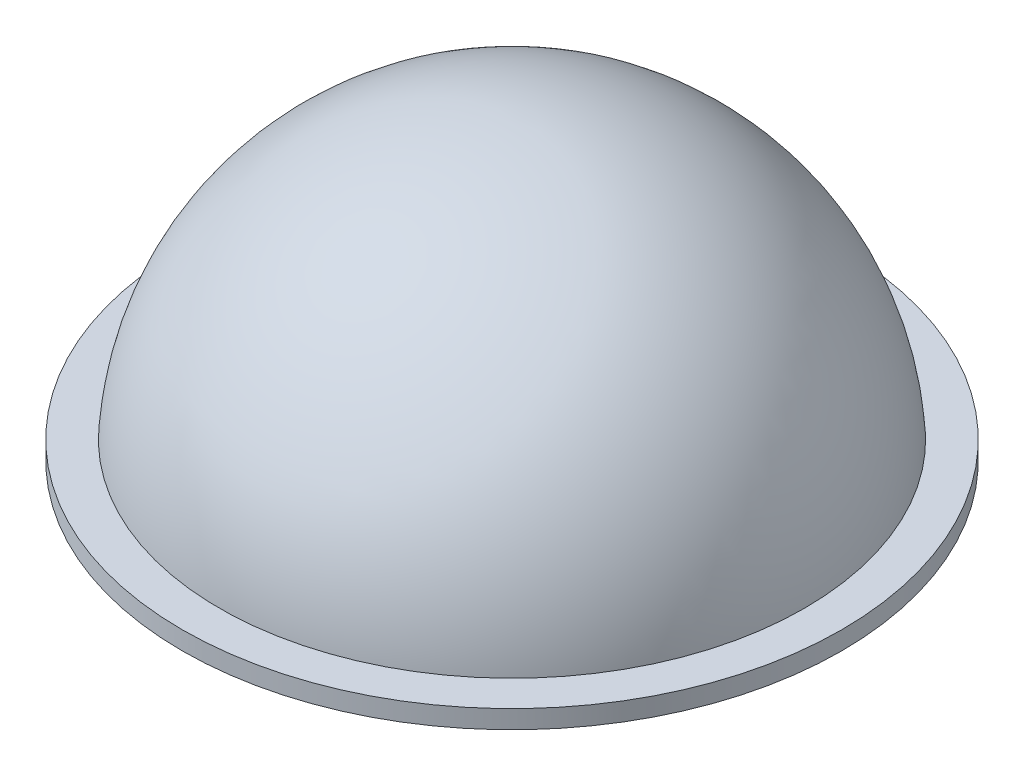
SolidWorks part; units mm, degrees
ref_plane "Front" through (0, 0, 0) normal (0, 0, 1) x (1, 0, 0)
ref_plane "Top" through (0, 0, 0) normal (0, 1, 0) x (1, 0, 0)
ref_plane "Right" through (0, 0, 0) normal (1, 0, 0) x (0, 0, -1)
sketch "Sketch1" plane through (0, 0, 0) normal (0, 0, 1) x (1, 0, 0)
  line L2 (-90, 0) -> (-90, 5)
  line L3 (-90, 5) -> (-79.8436, 5)
  line L8 (0, 0) -> (0, 80) construction
  line L9 (0, 80) -> (0, 75)
  line L10 (-90, 0) -> (80, 0) construction
  line L11 (-90, 0) -> (-75, 0)
  arc A0 (80, 0) -> (-80, 0) centre (0, 0) ccw construction
  arc A1 (0, 75) -> (-75, 0) centre (0, 0) ccw
  arc A2 (-79.8436, 5) -> (0, 80) centre (0, 0) cw
  point P1 (0, 0)
  dimension "D1" = 160
  dimension "D2" = 150
  dimension "D3" = 10
  dimension "D6" = 5
revolve "Revolve1" add sketch "Sketch1" angle 360 about L8
